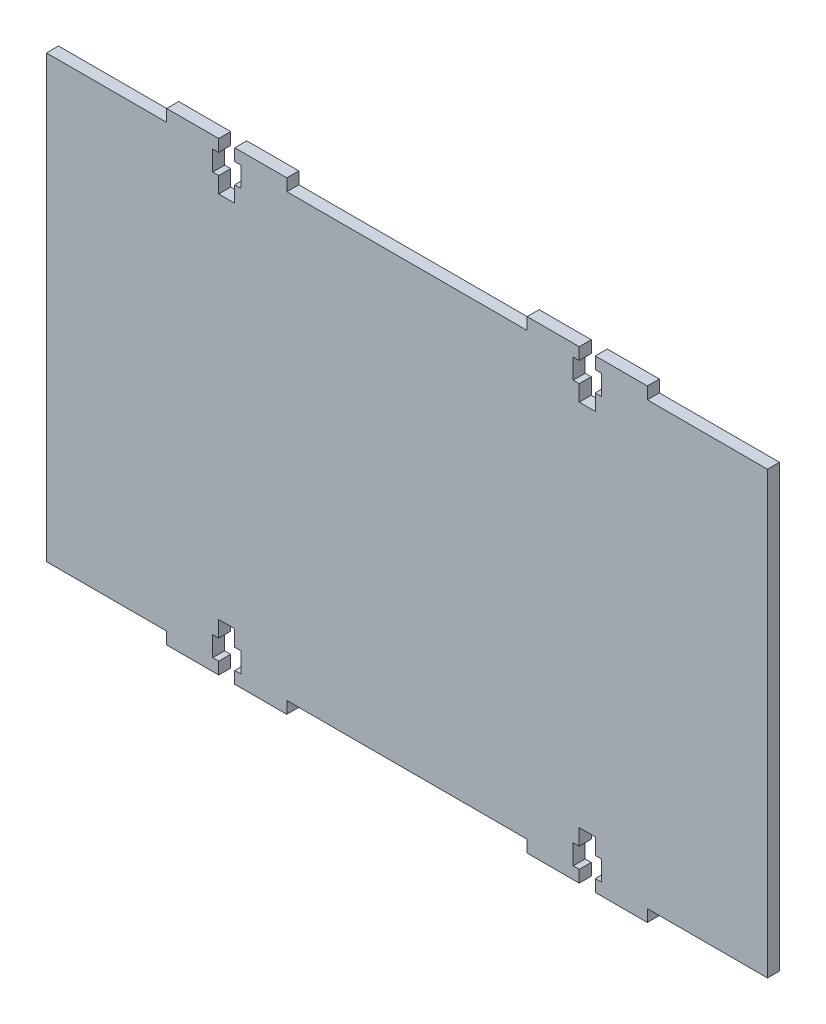
SolidWorks part; units mm, degrees
ref_plane "前视基准面" through (0, 0, 0) normal (0, 0, 1) x (1, 0, 0)
ref_plane "上视基准面" through (0, 0, 0) normal (0, 1, 0) x (1, 0, 0)
ref_plane "右视基准面" through (0, 0, 0) normal (1, 0, 0) x (0, 0, -1)
sketch "草图1" plane through (0, 0, 0) normal (0, 0, 1) x (1, 0, 0)
  line L0 (90, 0) -> (90, -110)
  line L1 (0, 0) -> (180, 0)
  line L2 (0, 0) -> (0, -110)
  line L3 (0, -110) -> (180, -110)
  line L4 (180, 0) -> (180, -110)
  line L5 (0, -55) -> (180, -55)
  line L6 (137, -9) -> (133, -9)
  line L7 (30, 0) -> (60, 0)
  line L8 (30, 0) -> (30, 3)
  line L9 (30, 3) -> (60, 3)
  line L10 (60, 0) -> (60, 3)
  line L11 (43, 3) -> (47, 3)
  line L12 (43, 3) -> (43, -9)
  line L13 (43, -9) -> (47, -9)
  line L14 (47, 3) -> (47, -9)
  line L15 (41.5, 0) -> (48.5, 0)
  line L16 (41.5, 0) -> (41.5, -5)
  line L17 (41.5, -5) -> (48.5, -5)
  line L18 (48.5, 0) -> (48.5, -5)
  line L19 (133, 3) -> (133, -9)
  line L20 (137, 3) -> (133, 3)
  line L21 (137, 3) -> (137, -9)
  line L22 (138.5, -5) -> (131.5, -5)
  line L23 (131.5, 0) -> (131.5, -5)
  line L24 (138.5, 0) -> (131.5, 0)
  line L25 (138.5, 0) -> (138.5, -5)
  line L26 (150, 3) -> (120, 3)
  line L27 (120, 0) -> (120, 3)
  line L28 (150, 0) -> (120, 0)
  line L29 (150, 0) -> (150, 3)
  line L30 (30, -113) -> (60, -113)
  line L31 (60, -110) -> (60, -113)
  line L32 (30, -110) -> (60, -110)
  line L33 (30, -110) -> (30, -113)
  line L34 (41.5, -105) -> (48.5, -105)
  line L35 (48.5, -110) -> (48.5, -105)
  line L36 (41.5, -110) -> (48.5, -110)
  line L37 (41.5, -110) -> (41.5, -105)
  line L38 (43, -101) -> (47, -101)
  line L39 (47, -113) -> (47, -101)
  line L40 (43, -113) -> (47, -113)
  line L41 (43, -113) -> (43, -101)
  line L42 (138.5, -110) -> (138.5, -105)
  line L43 (138.5, -110) -> (131.5, -110)
  line L44 (131.5, -110) -> (131.5, -105)
  line L45 (138.5, -105) -> (131.5, -105)
  line L46 (137, -113) -> (137, -101)
  line L47 (137, -113) -> (133, -113)
  line L48 (133, -113) -> (133, -101)
  line L49 (137, -101) -> (133, -101)
  line L50 (150, -110) -> (150, -113)
  line L51 (150, -110) -> (120, -110)
  line L52 (120, -110) -> (120, -113)
  line L53 (150, -113) -> (120, -113)
  dimension "D1" = 180
  dimension "D2" = 110
  dimension "D3" = 30
  dimension "D4" = 3
  dimension "D5" = 30
  dimension "D6" = 4
  dimension "D7" = 13
  dimension "D8" = 12
  dimension "D9" = 7
  dimension "D10" = 5
  dimension "D11" = 1.5
extrude "凸台-拉伸1" add sketch "草图1" along normal blind 3 contours L7 L18 L17 L14 L13 L12 L16 L1 L2 L5 L0 | L1 L25 L22 L21 L6 L19 L23 L0 L5 L4 | L49 L46 L45 L42 L3 L4 L5 L0 L44 L48 | L34 L41 L38 L39 L35 L32 L3 L0 L5 L2 L37 | L27 L1 L19 L26 | L1 L29 L26 L21 | L12 L9 L8 L1 L7 | L9 L14 L1 L7 L10 | L39 L30 L31 L32 L36 | L30 L41 L32 L3 L33 | L53 L50 L3 L43 L46 | L53 L48 L3 L52
